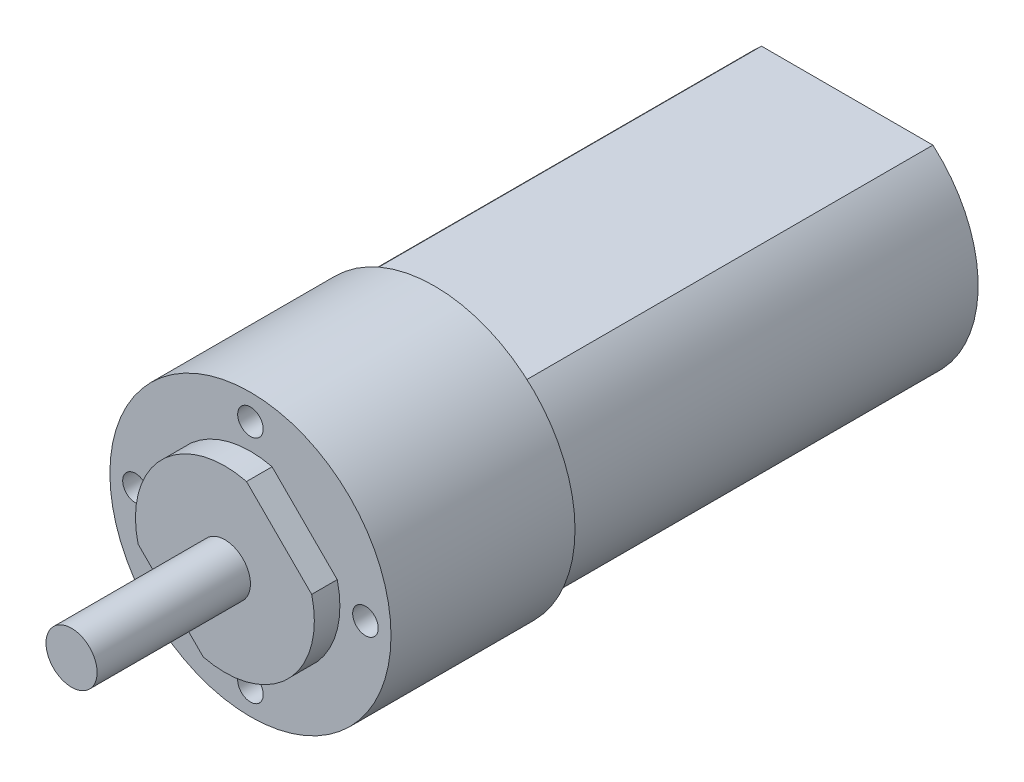
SolidWorks part; units mm, degrees
ref_plane "Plan de face" through (0, 0, 0) normal (0, 0, 1) x (1, 0, 0)
ref_plane "Plan de dessus" through (0, 0, 0) normal (0, 1, 0) x (1, 0, 0)
ref_plane "Plan de droite" through (0, 0, 0) normal (1, 0, 0) x (0, 0, -1)
sketch "Esquisse1" plane through (0, 0, 0) normal (0, 0, 1) x (1, 0, 0)
  line L0 (0, 17.0719) -> (0, -19.818) construction
  line L1 (19.1851, 0) -> (-18.7492, 0) construction
  line L2 (-18.7492, 7.75) -> (19.1851, 7.75) construction
  line L3 (19.1851, -7.75) -> (-18.7492, -7.75) construction
  line L4 (6.7082, -7.75) -> (-6.7082, -7.75)
  line L5 (-6.7082, 7.75) -> (6.7082, 7.75)
  circle A0 centre (0, 0) radius 10.25 construction
  arc A1 (6.7082, 7.75) -> (6.7082, -7.75) centre (0, 0) cw
  arc A2 (-6.7082, 7.75) -> (-6.7082, -7.75) centre (0, 0) ccw
  dimension "D1" = 20.5
  dimension "D2" = 7.75
  dimension "D3" = 7.75
extrude "Boss.-Extru.1" add sketch "Esquisse1" along normal blind 32.3
sketch "Esquisse2" plane through (0, 0, 32.3) normal (0, 0, 1) x (1, 0, 0)
  circle A0 centre (0, 0) radius 11
  dimension "D1" = 22
extrude "Boss.-Extru.2" add sketch "Esquisse2" along normal blind 14.4
sketch "Esquisse4" plane through (0, 0, 46.7) normal (0, 0, 1) x (1, 0, 0)
  line L0 (1.6931, 6.7922) -> (6.7922, 1.6931) construction
  line L1 (-1.6931, -6.7922) -> (-6.7922, -1.6931) construction
  line L2 (-1.6931, -6.7922) -> (-6.7922, -1.6931)
  line L3 (1.6931, 6.7922) -> (6.7922, 1.6931)
  line L4 (34.3237, 0) -> (-26.3979, 0) construction
  circle A0 centre (0, 0) radius 7 construction
  arc A1 (-6.7922, -1.6931) -> (1.6931, 6.7922) centre (0, 0) cw
  arc A2 (6.7922, 1.6931) -> (-1.6931, -6.7922) centre (0, 0) cw
  dimension "D1" = 14
  dimension "D2" = 6
  dimension "D3" = 6
  dimension "D4" = 45
extrude "Boss.-Extru.3" add sketch "Esquisse4" along normal blind 2
sketch "Esquisse5" plane through (0, 0, 48.7) normal (0, 0, 1) x (1, 0, 0)
  circle A0 centre (0, 0) radius 2
  dimension "D1" = 4
extrude "Boss.-Extru.4" add sketch "Esquisse5" along normal blind 12
sketch "Esquisse6" plane through (0, 0, 46.7) normal (0, 0, 1) x (1, 0, 0)
  line L0 (6.7922, 1.6931) -> (1.6931, 6.7922) construction
  line L1 (-7.7782, 7.7782) -> (7.7782, -7.7782) construction
  line L2 (-11, 0) -> (11, 0) construction
  line L3 (0, 11) -> (0, -11) construction
  circle A0 centre (0, 0) radius 11 construction
  circle A1 centre (0, 0) radius 9 construction
  circle A2 centre (-9, 0) radius 1
  circle A3 centre (0, 9) radius 1
  circle A4 centre (9, 0) radius 1
  circle A5 centre (0, -9) radius 1
  dimension "D2" = 18
  dimension "D3" = 2
  dimension "D1" = 45
extrude "Enlèv. mat.-Extru.1" cut sketch "Esquisse6" against normal blind 4
